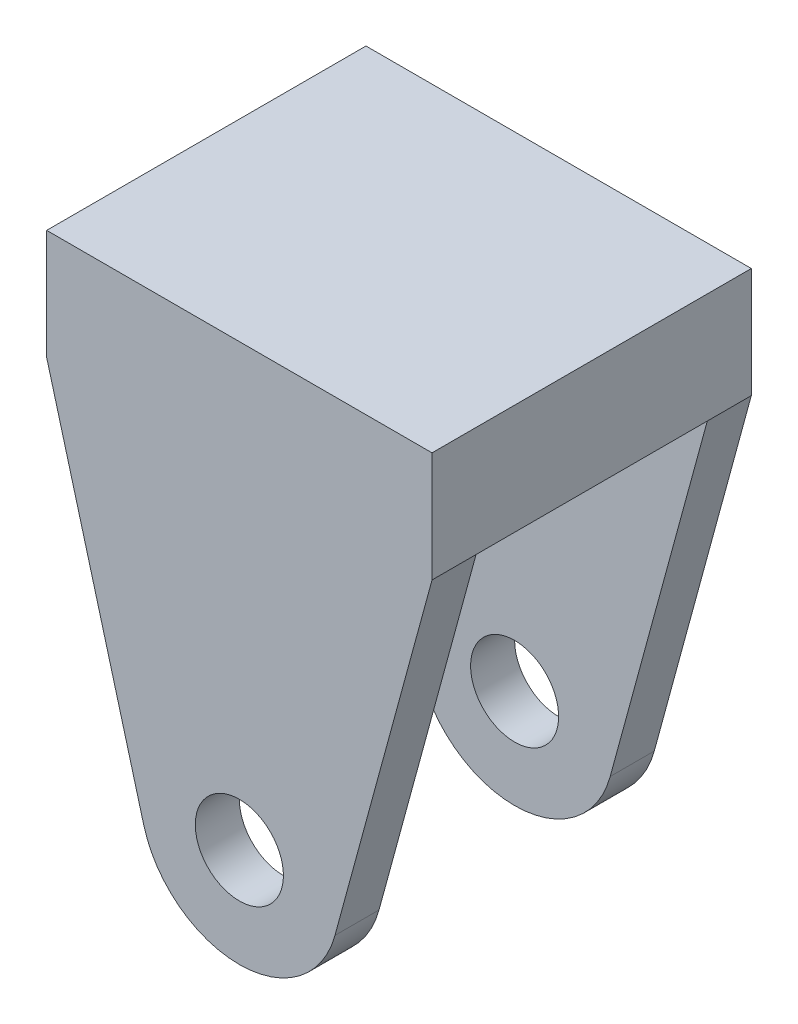
SolidWorks part; units mm, degrees
ref_plane "前视基准面" through (0, 0, 0) normal (0, 0, 1) x (1, 0, 0)
ref_plane "上视基准面" through (0, 0, 0) normal (0, 1, 0) x (1, 0, 0)
ref_plane "右视基准面" through (0, 0, 0) normal (1, 0, 0) x (0, 0, -1)
sketch "草图1" plane through (0, 0, 0) normal (0, 0, 1) x (1, 0, 0)
  line L0 (0, 0) -> (0, 60) construction
  line L2 (35, 60) -> (17.3673, -4.7309)
  line L3 (-35, 60) -> (-17.3673, -4.7309)
  line L4 (35, 60) -> (35, 80)
  line L5 (35, 80) -> (-35, 80)
  line L6 (-35, 80) -> (-35, 60)
  circle A0 centre (0, 0) radius 8
  arc A1 (-17.3673, -4.7309) -> (17.3673, -4.7309) centre (0, 0) ccw
extrude "凸台-拉伸1" add sketch "草图1" along normal mid plane 58
sketch "草图2" plane through (0, 0, 0) normal (0, 0, 1) x (1, 0, 0)
  line L0 (-35, 60) -> (35, 60)
  line L1 (35, 60) -> (17.3673, -4.7309)
  line L3 (-17.3673, -4.7309) -> (-35, 60)
  arc A0 (-17.3673, -4.7309) -> (17.3673, -4.7309) centre (0, 0) ccw
extrude "切除-拉伸1" cut sketch "草图2" against normal mid plane 42
